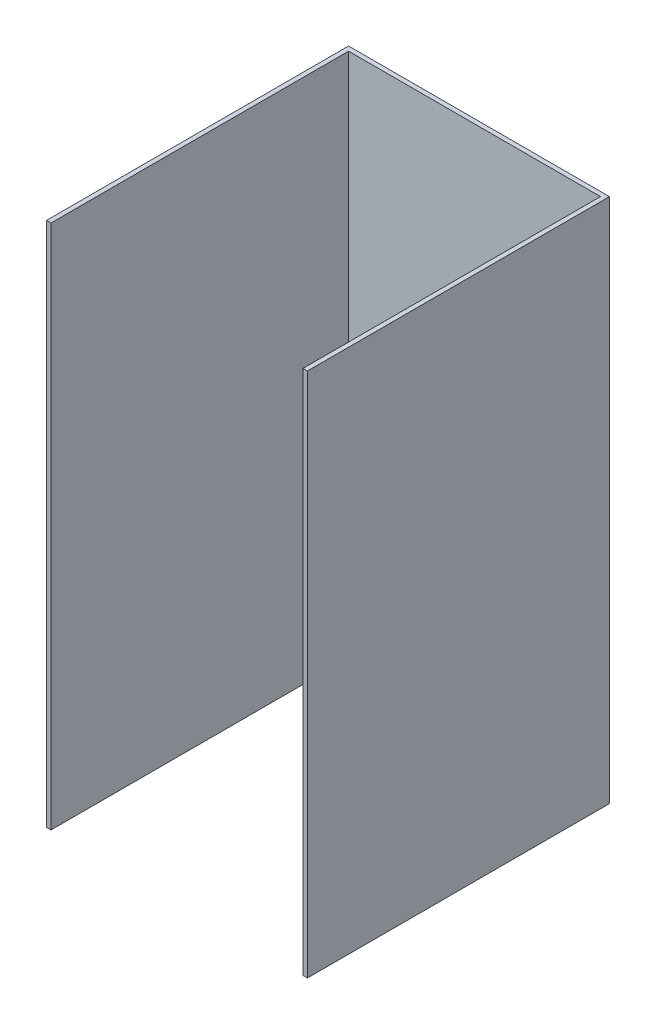
SolidWorks part; units mm, degrees
ref_plane "Front Plane" through (0, 0, 0) normal (0, 0, 1) x (1, 0, 0)
ref_plane "Top Plane" through (0, 0, 0) normal (0, 1, 0) x (1, 0, 0)
ref_plane "Right Plane" through (0, 0, 0) normal (1, 0, 0) x (0, 0, -1)
sketch "Sketch1" plane through (0, 0, 0) normal (0, 1, 0) x (1, 0, 0)
  line L0 (131.318, 2.286) -> (131.318, -152.4)
  line L1 (0, 0) -> (129.032, 0)
  line L2 (0, 0) -> (0, -152.4)
  line L3 (-2.286, 2.286) -> (131.318, 2.286)
  line L4 (129.032, 0) -> (129.032, -152.4)
  line L5 (-2.286, 2.286) -> (-2.286, -152.4)
  line L7 (-2.286, -152.4) -> (0, -152.4)
  line L9 (129.032, -152.4) -> (131.318, -152.4)
  dimension "D1" = 152.4
  dimension "D2" = 129.032
  dimension "D3" = 2.286
extrude "Boss-Extrude2" add sketch "Sketch1" along normal blind 269.24
